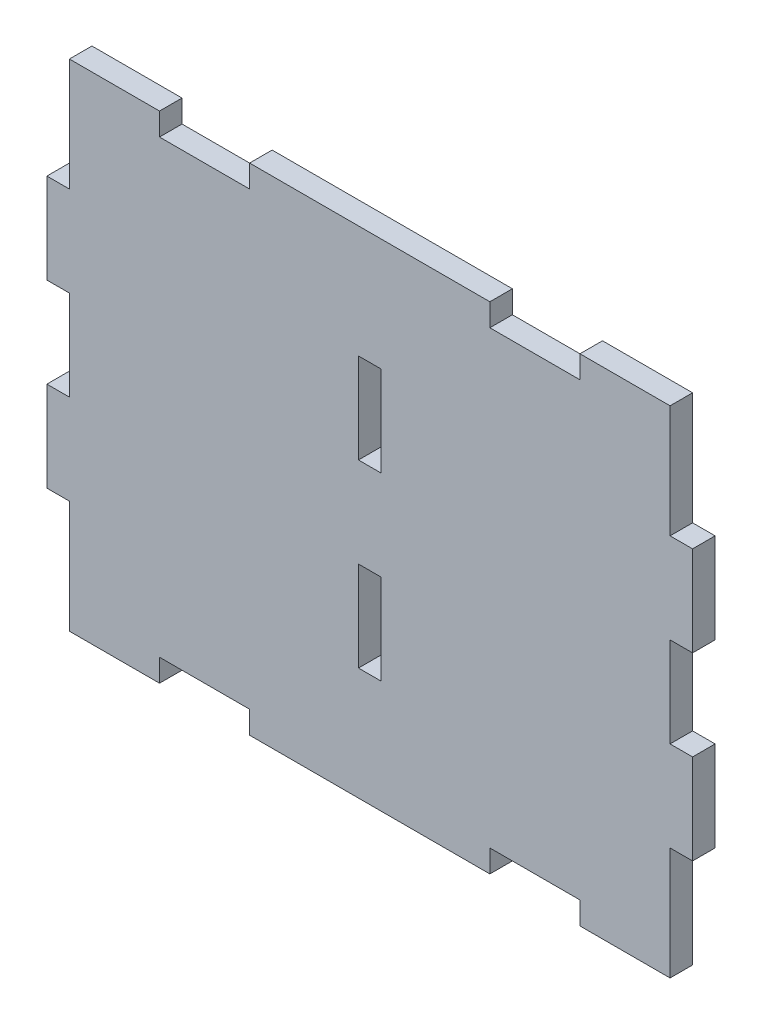
SolidWorks part; units mm, degrees
material "Pinho"
ref_plane "Plano frontal" through (0, 0, 0) normal (0, 0, 1) x (1, 0, 0)
ref_plane "Plano superior" through (0, 0, 0) normal (0, 1, 0) x (1, 0, 0)
ref_plane "Plano direito" through (0, 0, 0) normal (1, 0, 0) x (0, 0, -1)
sketch "Esboço1" plane through (0, 0, 0) normal (0, 0, 1) x (1, 0, 0)
  line L0 (-31.2169, 9.9098) -> (-31.2169, -2.0902)
  line L1 (-19.2169, 33.9098) -> (-7.2169, 33.9098)
  line L2 (-31.2169, 33.9098) -> (-31.2169, 21.9098)
  line L3 (-19.2169, -26.0902) -> (-7.2169, -26.0902)
  line L4 (48.7831, 33.9098) -> (48.7831, 21.9098)
  line L5 (-31.2169, -14.0902) -> (-31.2169, -26.0902)
  line L6 (-31.2169, 9.9098) -> (-34.2169, 9.9098)
  line L9 (-31.2169, 21.9098) -> (-34.2169, 21.9098)
  line L10 (-34.2169, 9.9098) -> (-34.2169, 21.9098)
  line L12 (-31.2169, 33.9098) -> (-31.2169, 36.9098)
  line L13 (-34.2169, -14.0902) -> (-31.2169, -14.0902)
  line L14 (-34.2169, -14.0902) -> (-34.2169, -2.0902)
  line L15 (-34.2169, -2.0902) -> (-31.2169, -2.0902)
  line L17 (-31.2169, 36.9098) -> (-19.2169, 36.9098)
  line L18 (-19.2169, 33.9098) -> (-19.2169, 36.9098)
  line L20 (48.7831, 33.9098) -> (48.7831, 36.9098)
  line L21 (48.7831, 36.9098) -> (36.7831, 36.9098)
  line L22 (36.7831, 33.9098) -> (36.7831, 36.9098)
  line L24 (-7.2169, 33.9098) -> (-7.2169, 36.9098)
  line L27 (48.7831, -14.0902) -> (48.7831, -26.0902)
  line L28 (48.7831, 9.9098) -> (51.7831, 9.9098)
  line L30 (48.7831, 21.9098) -> (51.7831, 21.9098)
  line L31 (51.7831, 9.9098) -> (51.7831, 21.9098)
  line L32 (24.7831, -26.0902) -> (36.7831, -26.0902)
  line L34 (48.7831, -14.0902) -> (51.7831, -14.0902)
  line L36 (48.7831, -2.0902) -> (51.7831, -2.0902)
  line L37 (51.7831, -14.0902) -> (51.7831, -2.0902)
  line L38 (48.7831, 9.9098) -> (48.7831, -2.0902)
  line L39 (-31.2169, -26.0902) -> (-31.2169, -29.0902)
  line L40 (-31.2169, -29.0902) -> (-19.2169, -29.0902)
  line L41 (-19.2169, -26.0902) -> (-19.2169, -29.0902)
  line L43 (48.7831, -26.0902) -> (48.7831, -29.0902)
  line L44 (48.7831, -29.0902) -> (36.7831, -29.0902)
  line L45 (36.7831, -26.0902) -> (36.7831, -29.0902)
  line L47 (-7.2169, -26.0902) -> (-7.2169, -29.0902)
  line L50 (24.7831, -26.0902) -> (24.7831, -29.0902)
  line L51 (24.7831, 33.9098) -> (24.7831, 36.9098)
  line L52 (7.2831, -2.0902) -> (10.2831, -2.0902)
  line L53 (7.2831, -2.0902) -> (7.2831, -14.0902)
  line L54 (7.2831, -14.0902) -> (10.2831, -14.0902)
  line L55 (10.2831, -2.0902) -> (10.2831, -14.0902)
  line L56 (7.2831, -2.0902) -> (10.2831, -14.0902) construction
  line L57 (7.2831, -14.0902) -> (10.2831, -2.0902) construction
  line L58 (7.2831, 21.9098) -> (10.2831, 21.9098)
  line L59 (7.2831, 21.9098) -> (7.2831, 9.9098)
  line L60 (7.2831, 9.9098) -> (10.2831, 9.9098)
  line L61 (10.2831, 21.9098) -> (10.2831, 9.9098)
  line L62 (7.2831, 21.9098) -> (10.2831, 9.9098) construction
  line L63 (7.2831, 9.9098) -> (10.2831, 21.9098) construction
  line L66 (24.7831, 33.9098) -> (36.7831, 33.9098)
  line L68 (24.7831, 36.9098) -> (-7.2169, 36.9098)
  line L70 (24.7831, -29.0902) -> (-7.2169, -29.0902)
  point P0 (0, 0)
  point P22 (8.7831, -8.0902)
  point P49 (8.7831, 15.9098)
  dimension "D1" = 60
  dimension "D2" = 80
  dimension "D3" = 12
  dimension "D4" = 12
  dimension "D5" = 12
  dimension "D6" = 12
  dimension "D7" = 12
  dimension "D8" = 40
  dimension "D9" = 12
  dimension "D10" = 12
  dimension "D11" = 12
  dimension "D12" = 12
  dimension "D13" = 12
  dimension "D14" = 12
  dimension "D16" = 12
  dimension "D17" = 3
  dimension "D18" = 3
  dimension "D19" = 3
  dimension "D20" = 3
  dimension "D21" = 3
  dimension "D22" = 3
  dimension "D23" = 3
  dimension "D24" = 3
  dimension "D25" = 40
  dimension "D26" = 3
  dimension "D27" = 3
  dimension "D28" = 3
  dimension "D29" = 3
  dimension "D30" = 12
  dimension "D31" = 3
  dimension "D32" = 12
  dimension "D33" = 12
  dimension "D35" = 12
  dimension "D36" = 3
  dimension "D37" = 3
  dimension "D38" = 12
extrude "Ressalto-extrusão1" add sketch "Esboço1" along normal blind 3
